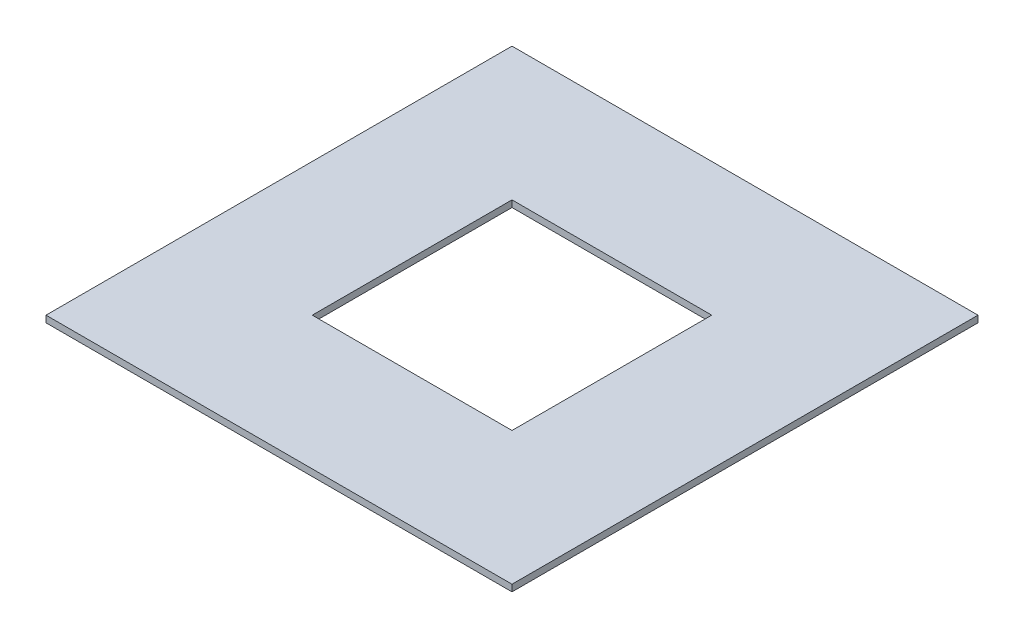
SolidWorks part; units mm, degrees
ref_plane "Front Plane" through (0, 0, 0) normal (0, 0, 1) x (1, 0, 0)
ref_plane "Top Plane" through (0, 0, 0) normal (0, 1, 0) x (1, 0, 0)
ref_plane "Right Plane" through (0, 0, 0) normal (1, 0, 0) x (0, 0, -1)
sketch "Sketch4" plane through (0, 0, 0) normal (0, 1, 0) x (1, 0, 0)
  line L0 (-100.6481, 115.9032) -> (-100.6481, 65.1032)
  line L1 (-100.6481, 115.9032) -> (77.1519, 115.9032)
  line L2 (-100.6481, 115.9032) -> (-100.6481, -61.8968)
  line L3 (-100.6481, -61.8968) -> (77.1519, -61.8968)
  line L4 (77.1519, 115.9032) -> (77.1519, -61.8968)
  line L6 (77.1519, 65.1032) -> (77.1519, 115.9032)
  line L7 (-49.8481, 65.1032) -> (26.3519, 65.1032)
  line L9 (-49.8481, 65.1032) -> (26.3519, 65.1032)
  line L10 (-49.8481, 65.1032) -> (-49.8481, -11.0968)
  line L11 (-49.8481, -11.0968) -> (26.3519, -11.0968)
  line L12 (26.3519, 65.1032) -> (26.3519, -11.0968)
  point P9 (-11.7481, 65.1032)
extrude "Boss-Extrude2" add sketch "Sketch4" against normal blind 2.54 contours L2 L1 L4 L3
sketch "Sketch5" plane through (0, 0, 0) normal (0, 1, 0) x (1, 0, 0)
  line L0 (-100.6481, 115.9032) -> (-100.6481, 65.1032)
  line L1 (-100.6481, 115.9032) -> (-100.6481, -61.8968) construction
  line L3 (77.1519, 115.9032) -> (77.1519, -61.8968) construction
  line L4 (77.1519, 65.1032) -> (77.1519, 115.9032)
  line L5 (-49.8481, 65.1032) -> (26.3519, 65.1032)
  line L7 (-49.8481, 65.1032) -> (26.3519, 65.1032)
  line L8 (-49.8481, 65.1032) -> (-49.8481, -11.0968)
  line L9 (-49.8481, -11.0968) -> (26.3519, -11.0968)
  line L10 (26.3519, 65.1032) -> (26.3519, -11.0968)
  point P13 (-11.7481, 65.1032)
extrude "Cut-Extrude1" cut sketch "Sketch5" against normal blind 84.074 contours L8 L7 L10 L9
sketch "Sketch6" plane through (0, 0, 0) normal (0, 1, 0) x (1, 0, 0)
  point P14 (-11.7481, 65.1032)
  point P17 (-11.7481, 46.0532)
